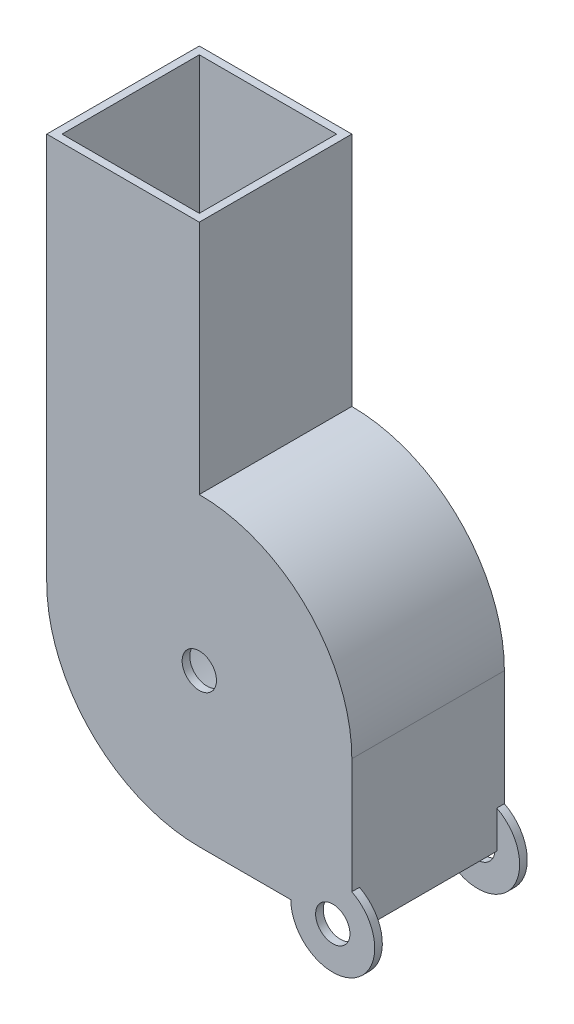
SolidWorks part; units mm, degrees
ref_plane "Front Plane" through (0, 0, 0) normal (0, 0, 1) x (1, 0, 0)
ref_plane "Top Plane" through (0, 0, 0) normal (0, 1, 0) x (1, 0, 0)
ref_plane "Right Plane" through (0, 0, 0) normal (1, 0, 0) x (0, 0, -1)
sketch "Sketch1" plane through (0, 0, 0) normal (0, 0, 1) x (1, 0, 0)
  line L0 (-40, 0) -> (-40, 101.8559)
  line L1 (-40, 101.8559) -> (0, 101.8559)
  line L2 (0, 101.8559) -> (0, 40)
  line L6 (0, -40) -> (40, -40)
  line L7 (40, 0) -> (40, -40)
  arc A0 (-40, 0) -> (0, -40) centre (0, 0) ccw
  arc A1 (40, 0) -> (0, 40) centre (0, 0) ccw
extrude "Boss-Extrude1" add sketch "Sketch1" along normal blind 40
shell "Shell1" thickness 2
sketch "Sketch2" plane through (0, -40, 0) normal (0, -1, 0) x (1, 0, 0)
  line L0 (2, 38) -> (2, 2)
  line L1 (2, 2) -> (38, 2)
  line L2 (38, 2) -> (38, 38)
  line L3 (38, 38) -> (2, 38)
extrude "Cut-Extrude1" cut sketch "Sketch2" against normal blind 40
sketch "Sketch3" plane through (0, 0, 40) normal (0, 0, 1) x (1, 0, 0)
  circle A0 centre (40, -40) radius 8.546
extrude "Boss-Extrude2" [suppressed] add sketch "Sketch3" against normal blind 40
fillet "Fillet1" [suppressed] radius 10
sketch "Sketch4" [suppressed] plane through (0, 0, 40) normal (0, 0, 1) x (1, 0, 0)
  line L0 (31.454, -40) -> (40, -40) construction
  circle A0 centre (40, -40) radius 5
extrude "Cut-Extrude2" [suppressed] cut sketch "Sketch4" against normal blind 40
fillet "Fillet2" [suppressed] radius 10
fillet "Fillet3" [suppressed] radius 1
sketch "Sketch5" plane through (0, 0, 40) normal (0, 0, 1) x (1, 0, 0)
  circle A0 centre (0.2787, 0.4151) radius 39.5
ref_plane "Plane1" through (0, -40, 0) normal (0, -1, 0) x (-1, 0, 0)
sketch "Sketch6" [suppressed] plane through (0, -40, 0) normal (0, -1, 0) x (-1, 0, 0)
  line L0 (24.7916, -33.5) -> (9.379, -33.5) construction
  line L1 (24.7916, -35) -> (9.379, -35)
  line L2 (24.7916, -32) -> (9.379, -32)
  line L3 (24.7916, -6.5) -> (9.379, -6.5) construction
  line L4 (24.7916, -8) -> (9.379, -8)
  line L5 (24.7916, -5) -> (9.379, -5)
  line L6 (24.7916, -24.5) -> (9.379, -24.5) construction
  line L7 (24.7916, -26) -> (9.379, -26)
  line L8 (24.7916, -23) -> (9.379, -23)
  line L9 (24.7916, -15.5) -> (9.379, -15.5) construction
  line L10 (24.7916, -17) -> (9.379, -17)
  line L11 (24.7916, -14) -> (9.379, -14)
  line L12 (0, -39) -> (40, -39) construction
  line L13 (40, -1) -> (0, -1) construction
  arc A0 (24.7916, -35) -> (24.7916, -32) centre (24.7916, -33.5) ccw
  arc A1 (9.379, -32) -> (9.379, -35) centre (9.379, -33.5) ccw
  arc A2 (24.7916, -8) -> (24.7916, -5) centre (24.7916, -6.5) ccw
  arc A3 (9.379, -5) -> (9.379, -8) centre (9.379, -6.5) ccw
  arc A4 (24.7916, -26) -> (24.7916, -23) centre (24.7916, -24.5) ccw
  arc A5 (9.379, -23) -> (9.379, -26) centre (9.379, -24.5) ccw
  arc A6 (24.7916, -17) -> (24.7916, -14) centre (24.7916, -15.5) ccw
  arc A7 (9.379, -14) -> (9.379, -17) centre (9.379, -15.5) ccw
  point P2 (17.0853, -33.5)
  point P7 (17.0853, -6.5)
  point P14 (17.0853, -24.5)
  point P21 (17.0853, -15.5)
  dimension "D1" = 1.5
  dimension "D2" = 1.5
  dimension "D3" = 1.5
  dimension "D4" = 1.5
  dimension "D5" = 4
  dimension "D6" = 4
  dimension "D7" = 6
  dimension "D8" = 6
extrude "Cut-Extrude3" [suppressed] cut sketch "Sketch6" against normal blind 40
sketch "Sketch7" plane through (0, 0, 40) normal (0, 0, 1) x (1, 0, 0)
  line L2 (40, -40) -> (40, 0) construction
  circle A0 centre (35, -40) radius 11
  dimension "D1" = 22
  dimension "D2" = 5
extrude "Boss-Extrude3" add sketch "Sketch7" against normal up to surface (2 mm away) up to face at (0.0315, 9.5982, 38)
sketch "Sketch8" plane through (0, 0, 40) normal (0, 0, 1) x (1, 0, 0)
  circle A0 centre (0, 0) radius 4.5
  dimension "D1" = 9
extrude "Cut-Extrude4" cut sketch "Sketch8" against normal up to surface (40 mm away) up to face at (0, 23.3874, 0)
sketch "Sketch9" plane through (0, 0, 0) normal (0, 0, -1) x (-1, 0, 0)
  circle A0 centre (-35, -40) radius 11
extrude "Boss-Extrude4" add sketch "Sketch9" against normal up to surface (2 mm away) up to face at (4.5, 0, 2)
sketch "Sketch10" plane through (0, 0, 40) normal (0, 0, 1) x (1, 0, 0)
  circle A0 centre (35, -40) radius 4.5
extrude "Cut-Extrude5" cut sketch "Sketch10" against normal through all
